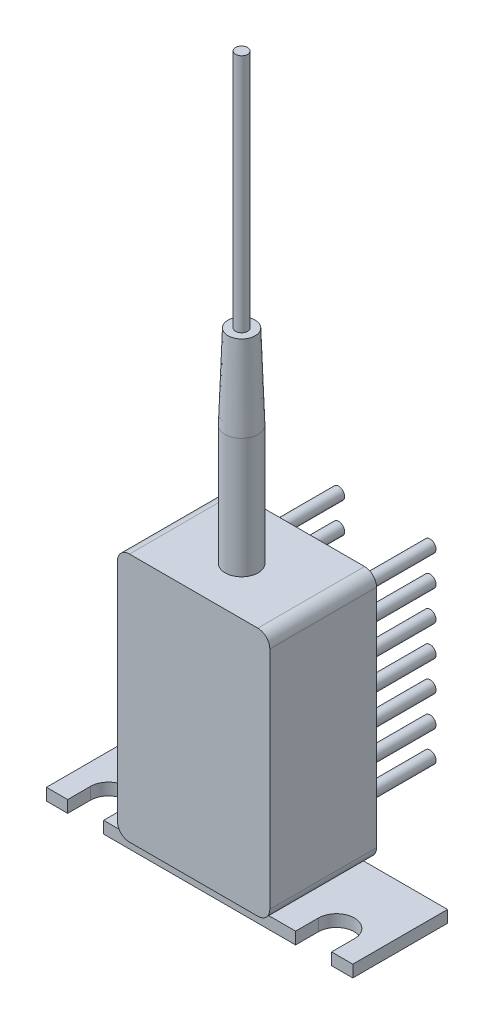
SolidWorks part; units mm, degrees
ref_plane "前视基准面" through (0, 0, 0) normal (0, 0, 1) x (1, 0, 0)
ref_plane "上视基准面" through (0, 0, 0) normal (0, 1, 0) x (1, 0, 0)
ref_plane "右视基准面" through (0, 0, 0) normal (1, 0, 0) x (0, 0, -1)
sketch "草图1" plane through (0, 0, 0) normal (0, 0, 1) x (1, 0, 0)
  line L0 (13.1116, 0) -> (-17.4658, 0) construction
  line L1 (-6.35, 10.4) -> (6.35, 10.4)
  line L2 (-6.35, 10.4) -> (-6.35, -10.4)
  line L3 (-6.35, -10.4) -> (6.35, -10.4)
  line L4 (6.35, 10.4) -> (6.35, -10.4)
  line L5 (0, -15.7941) -> (0, 20.7915) construction
  dimension "D1" = 12.7
  dimension "D2" = 20.8
extrude "凸台-拉伸1" add sketch "草图1" along normal blind 8.9
sketch "草图2" plane through (0, 0, 0) normal (0, 0, -1) x (-1, 0, 0)
  line L0 (0, 14.7113) -> (0, -15.9166) construction
  line L1 (12.2748, 0) -> (-10.5543, 0) construction
  circle A0 centre (-3.81, 0) radius 0.5
  circle A1 centre (-3.81, 2.54) radius 0.5
  circle A2 centre (-3.81, 5.08) radius 0.5
  circle A3 centre (-3.81, 7.62) radius 0.5
  circle A4 centre (-3.81, -2.54) radius 0.5
  circle A5 centre (-3.81, -5.08) radius 0.5
  circle A6 centre (-3.81, -7.62) radius 0.5
  circle A7 centre (3.81, -7.62) radius 0.5
  circle A8 centre (3.81, -5.08) radius 0.5
  circle A9 centre (3.81, -2.54) radius 0.5
  circle A10 centre (3.81, 7.62) radius 0.5
  circle A11 centre (3.81, 5.08) radius 0.5
  circle A12 centre (3.81, 2.54) radius 0.5
  circle A13 centre (3.81, 0) radius 0.5
  dimension "D1" = 1
  dimension "D4" = 7.62
  dimension "D2" = 4
  dimension "D3" = 4
extrude "凸台-拉伸2" add sketch "草图2" along normal blind 7
fillet "圆角1" radius 1 4 edges at (-6.35, 10.4, 4.45) (6.35, 10.4, 4.45) (-6.35, -10.4, 4.45) (6.35, -10.4, 4.45)
sketch "草图3" plane through (0, -10.4, 0) normal (0, -1, 0) x (1, 0, 0)
  line L1 (-12.77, 8.4) -> (12.77, 8.4)
  line L2 (-12.77, 8.4) -> (-12.77, 0.5)
  line L3 (-12.77, 0.5) -> (12.77, 0.5)
  line L4 (12.77, 8.4) -> (12.77, 0.5)
  line L5 (-5.35, 0) -> (5.35, 0) construction
  line L6 (-5.35, 8.9) -> (5.35, 8.9) construction
  line L7 (0, -2.4036) -> (0, 11.393) construction
  dimension "D1" = 25.54
  dimension "D2" = 0.5
  dimension "D3" = 0.5
extrude "凸台-拉伸3" add sketch "草图3" along normal blind 1
sketch "草图4" plane through (0, -11.4, 0) normal (0, -1, 0) x (1, 0, 0)
  line L0 (-14.2228, 6.5) -> (16.1089, 6.5) construction
  line L1 (-5.35, 0) -> (5.35, 0) construction
  line L2 (0, -4.273) -> (0, 10.4069) construction
  line L3 (9.5, 9.863) -> (9.5, 3.748) construction
  line L4 (8, 6.5) -> (8, 8.4)
  line L5 (12.77, 8.4) -> (-12.77, 8.4) construction
  line L6 (11, 6.5) -> (11, 8.4)
  line L7 (8, 8.4) -> (11, 8.4)
  line L8 (-9.5, 9.863) -> (-9.5, 3.748) construction
  line L9 (-8, 8.4) -> (-11, 8.4)
  line L10 (-11, 6.5) -> (-11, 8.4)
  line L11 (-8, 6.5) -> (-8, 8.4)
  arc A0 (8, 6.5) -> (11, 6.5) centre (9.5, 6.5) ccw
  arc A1 (-8, 6.5) -> (-11, 6.5) centre (-9.5, 6.5) cw
  dimension "D2" = 1.5
  dimension "D1" = 6.5
  dimension "D3" = 19
extrude "切除-拉伸1" cut sketch "草图4" against normal through all
sketch "草图5" plane through (0, 10.4, 0) normal (0, 1, 0) x (1, 0, 0)
  line L0 (0, 8.2762) -> (0, -12.7922) construction
  line L1 (-15.9064, -4.9) -> (17.9152, -4.9) construction
  line L2 (5.35, -8.9) -> (-5.35, -8.9) construction
  circle A0 centre (0, -4.9) radius 1.375
  dimension "D1" = 2.75
  dimension "D2" = 4
extrude "凸台-拉伸4" add sketch "草图5" along normal blind 17
chamfer "倒角1" distance 7 angle 2 1 edges at (0, 27.4, 6.275)
sketch "草图7" plane through (0, 27.4, 0) normal (0, 1, 0) x (1, 0, 0)
  circle A0 centre (0, -4.9) radius 0.5
  dimension "D1" = 1
extrude "凸台-拉伸5" add sketch "草图7" along normal blind 20
